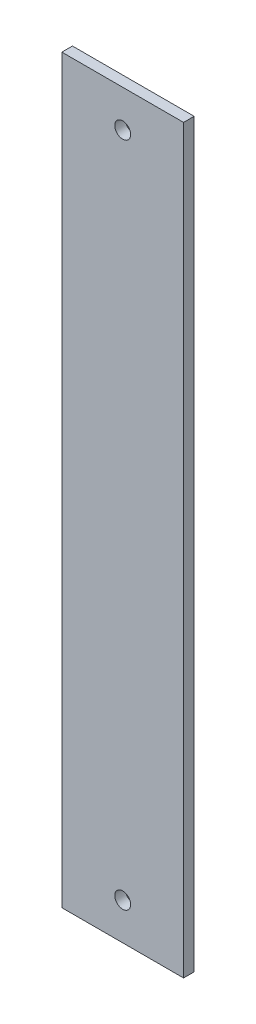
SolidWorks part; units mm, degrees
ref_plane "Front Plane" through (0, 0, 0) normal (0, 0, 1) x (1, 0, 0)
ref_plane "Top Plane" through (0, 0, 0) normal (0, 1, 0) x (1, 0, 0)
ref_plane "Right Plane" through (0, 0, 0) normal (1, 0, 0) x (0, 0, -1)
sketch "Sketch2" plane through (0, 0, 0) normal (0, 0, 1) x (1, 0, 0)
  line L0 (11.5, 140) -> (11.5, 0) construction
  line L1 (0, 0) -> (23, 0)
  line L2 (0, 0) -> (0, 140)
  line L3 (0, 140) -> (23, 140)
  line L4 (23, 0) -> (23, 140)
  circle A0 centre (11.5, 133) radius 1.5
  circle A1 centre (11.5, 7) radius 1.5
  dimension "D3" = 3
  dimension "D5" = 3
  dimension "D1" = 140
  dimension "D2" = 23
  dimension "D4" = 7
  dimension "D6" = 7
extrude "Boss-Extrude1" add sketch "Sketch2" along normal blind 2
